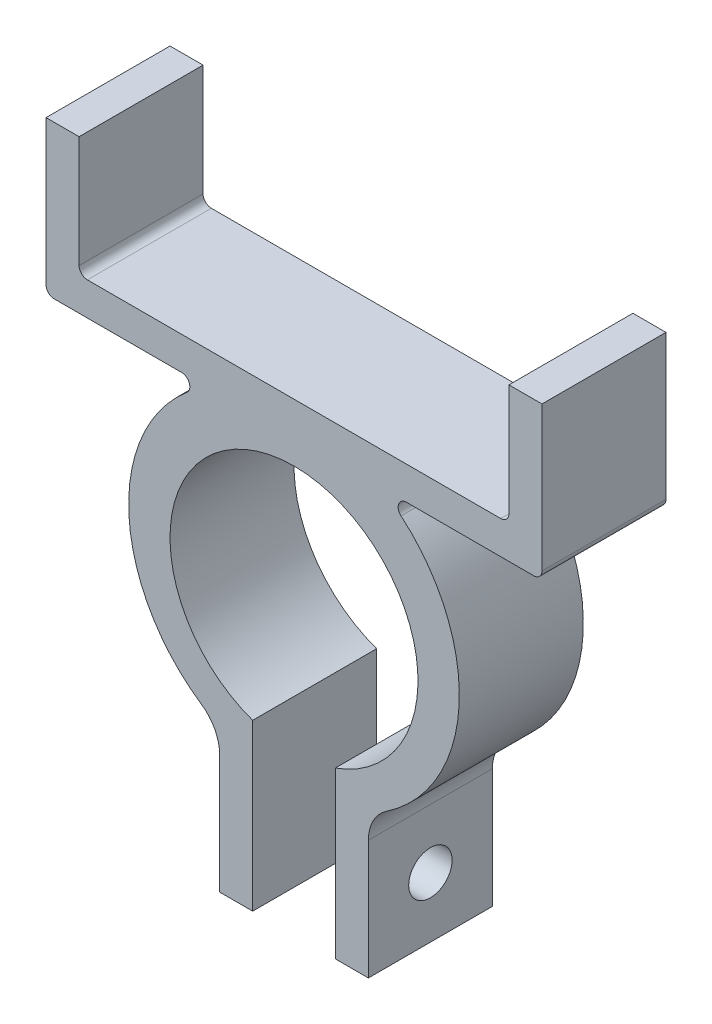
SolidWorks part; units mm, degrees
material "Custom Plastic"
ref_plane "Front Plane" through (0, 0, 0) normal (0, 0, 1) x (1, 0, 0)
ref_plane "Top Plane" through (0, 0, 0) normal (0, 1, 0) x (1, 0, 0)
ref_plane "Right Plane" through (0, 0, 0) normal (1, 0, 0) x (0, 0, -1)
sketch "Sketch1" plane through (0, 0, 0) normal (0, 0, 1) x (1, 0, 0)
  line L0 (0, 0) -> (0, -1) construction
  line L1 (0, 0) -> (-5, 0) construction
  line L2 (0, 0) -> (5, 0) construction
  line L3 (-5, 0) -> (-5, -15.1421) construction
  line L4 (5, 0) -> (5, -15.1421) construction
  line L5 (-5, -15.1421) -> (-5, -20.9762) construction
  line L6 (5, -15.1421) -> (5, -19.3649) construction
  line L7 (-5, -15.1421) -> (-5, -20.9762)
  line L10 (-5, -15.1421) -> (-9, -15.1421)
  line L11 (-5, -15.1421) -> (-5, -35.1421)
  line L12 (-9, -15.1421) -> (-9, -35.1421)
  line L13 (-5, -35.1421) -> (-9, -35.1421)
  line L14 (5, -15.1421) -> (9, -15.1421)
  line L15 (5, -15.1421) -> (5, -35.1421)
  line L16 (9, -15.1421) -> (9, -35.1421)
  line L17 (5, -35.1421) -> (9, -35.1421)
  line L18 (-9, -35.1421) -> (-2.2453, -35.1421) construction
  line L19 (0, 17) -> (0, 21) construction
  line L20 (-30, 17) -> (30, 17)
  line L21 (-30, 17) -> (-30, 21)
  line L23 (-30, 21) -> (30, 21)
  line L24 (30, 17) -> (30, 21)
  line L26 (0, 0) -> (0, 17) construction
  line L29 (-30, 21) -> (-26, 21)
  line L30 (-30, 21) -> (-30, 35.5)
  line L31 (-30, 35.5) -> (-26, 35.5)
  line L32 (-26, 21) -> (-26, 35.5)
  line L34 (30, 21) -> (26, 21)
  line L35 (30, 21) -> (30, 35.5)
  line L36 (30, 35.5) -> (26, 35.5)
  line L37 (26, 21) -> (26, 35.5)
  circle A1 centre (0, -1) radius 15
  arc A2 (-5, -15.1421) -> (5, -15.1421) centre (0, 0) ccw
  circle A5 centre (0, 0) radius 20
  dimension "D3" = 30
  dimension "D12" = 4
  dimension "D13" = 14.5
  dimension "D14" = 14.5
  dimension "D17" = 40
  dimension "D2" = 1
  dimension "D4" = 5
  dimension "D5" = 5
  dimension "D7" = 20
  dimension "D8" = 4
  dimension "D9" = 4
  dimension "D10" = 17
  dimension "D11" = 60
  dimension "D15" = 4
  dimension "D16" = 4
extrude "Boss-Extrude1" add sketch "Sketch1" along normal blind 15
sketch "Sketch2" plane through (9, 0, 0) normal (1, 0, 0) x (0, 0, -1)
  line L0 (0, -17.8606) -> (0, -35.1421) construction
  circle A0 centre (-7.5, -27.8606) radius 2.625
  dimension "D1" = 5.25
  dimension "D2" = 7.5
  dimension "D3" = 10
extrude "Cut-Extrude1" cut sketch "Sketch2" against normal blind 10
ref_plane "Plane1" through (9, -17.8606, 15) normal (0, 0, 1) x (1, 0, 0)
fillet "Fillet3" radius 5 2 edges at (-9, -17.8606, 7.5) (9, -17.8606, 7.5)
fillet "Fillet5" radius 1 2 edges at (10.5357, 17, 7.5) (-10.5357, 17, 7.5)
fillet "Fillet6" radius 1 4 edges at (-26, 21, 7.5) (26, 21, 7.5) (30, 17, 7.5) (-30, 17, 7.5)
sketch "Sketch3" plane through (30, 0, 0) normal (1, 0, 0) x (0, 0, -1)
  line L0 (0, 15.2381) -> (-15, 15.2381) construction
  circle A0 centre (-7.5, 15.2381) radius 1.5
  dimension "D1" = 3
extrude "Cut-Extrude4" cut sketch "Sketch3" against normal blind 58
